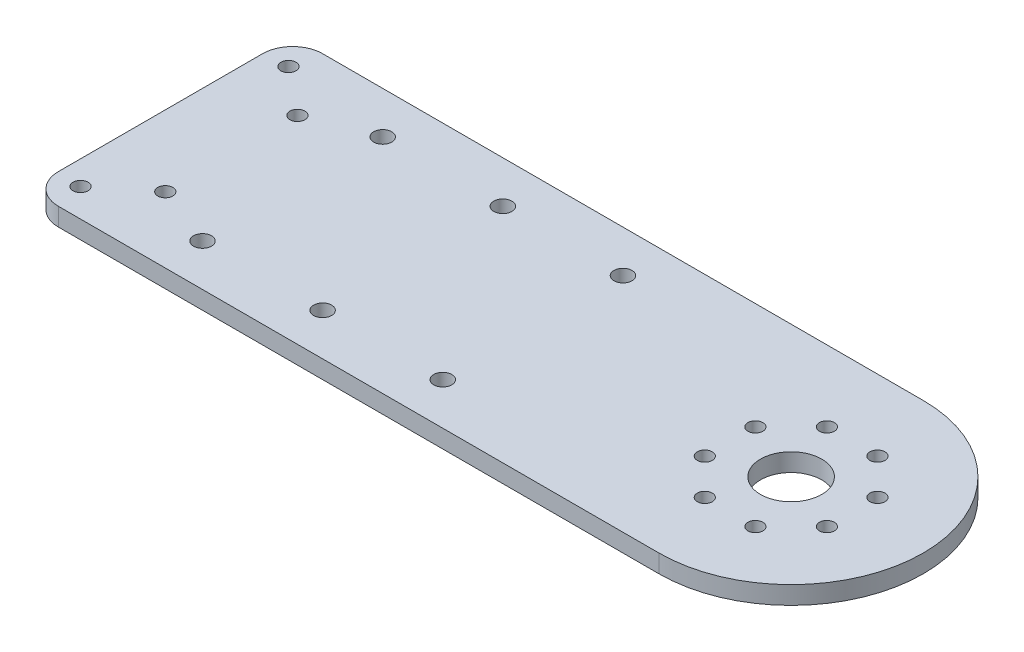
SolidWorks part; units mm, degrees
ref_plane "Front" through (0, 0, 0) normal (0, 0, 1) x (1, 0, 0)
ref_plane "Top" through (0, 0, 0) normal (0, 1, 0) x (1, 0, 0)
ref_plane "Right" through (0, 0, 0) normal (1, 0, 0) x (0, 0, -1)
sketch "Sketch1" plane through (0, 0, 0) normal (0, 1, 0) x (1, 0, 0)
  line L0 (0, 0) -> (128, 0) construction
  line L1 (128, 0) -> (117.8373, 4.2095) construction
  line L2 (128, 22) -> (0, 22)
  line L3 (0, 22) -> (0, 16.4924)
  line L4 (0, -22) -> (128, -22)
  line L5 (0, 0) -> (-13, 0) construction
  line L6 (0, -16.4924) -> (0, -22)
  line L7 (5, 17.3) -> (27, 17.3) construction
  circle A0 centre (128, 0) radius 5.1
  circle A1 centre (117.8373, 4.2095) radius 1.25
  arc A2 (128, -22) -> (128, 22) centre (128, 0) ccw
  circle A3 centre (123.7905, 10.1627) radius 1.25
  circle A4 centre (132.2095, 10.1627) radius 1.25
  circle A5 centre (138.1627, 4.2095) radius 1.25
  circle A6 centre (138.1627, -4.2095) radius 1.25
  circle A7 centre (132.2095, -10.1627) radius 1.25
  arc A8 (0, -16.4924) -> (0, 16.4924) centre (-13, 0) ccw
  circle A9 centre (5, 17.3) radius 1.25
  circle A10 centre (27, 17.3) radius 1.25
  circle A11 centre (27, -17.3) radius 1.25
  circle A12 centre (5, -17.3) radius 1.25
  circle A13 centre (123.7905, -10.1627) radius 1.25
  circle A14 centre (117.8373, -4.2095) radius 1.25
  circle A15 centre (34.8, 11) radius 1.25
  circle A16 centre (34.8, -11) radius 1.25
  point P19 (128, 0)
  dimension "D1" = 2.5
  dimension "D2" = 10.2
  dimension "D4" = 44
  dimension "D9" = 42
  dimension "D10" = 2.5
  dimension "D11" = 2.5
  dimension "D15" = 2.5
  dimension "D16" = 11
  dimension "D17" = 7.8
  dimension "D3" = 11
  dimension "D5" = 22.5
  dimension "D7" = 128
  dimension "D8" = 13
  dimension "D12" = 22
  dimension "D13" = 17.3
  dimension "D14" = 5
  dimension "D6" = 8
extrude "Boss-Extrude1" add sketch "Sketch1" along normal blind 3
fillet "Fillet1" radius 1.5 4 edges at (0, 1.5, -22) (0, 1.5, 22) (0, 1.5, 16.4924) (0, 1.5, -16.4924)
sketch "Sketch2" plane through (0, 3, 0) normal (0, 1, 0) x (1, 0, 0)
  line L0 (0, 0) -> (128, 0) construction
  circle A0 centre (47, 0) radius 1.5
  circle A1 centre (69, 0) radius 1.5
  circle A2 centre (27, -17.3) radius 1.25 construction
  dimension "D1" = 3
  dimension "D2" = 3
  dimension "D3" = 22
  dimension "D4" = 20
extrude "Cut-Extrude1" [suppressed] cut sketch "Sketch2" against normal blind 3
sketch "Sketch3" plane through (0, 3, 0) normal (0, 1, 0) x (1, 0, 0)
  line L0 (1.6969, 15) -> (121.5816, 15) construction
  line L1 (0, 0) -> (128, 0) construction
  arc A0 (0.5333, -16.0577) -> (0.5333, 16.0577) centre (-13, 0) ccw construction
  circle A1 centre (45, 15) radius 1.5
  circle A2 centre (65, 15) radius 1.5
  circle A3 centre (85, 15) radius 1.5
  circle A4 centre (85, -15) radius 1.5
  circle A5 centre (65, -15) radius 1.5
  circle A6 centre (45, -15) radius 1.5
  dimension "D1" = 3
  dimension "D2" = 15
  dimension "D3" = 45
  dimension "D4" = 3
extrude "Cut-Extrude2" cut sketch "Sketch3" against normal blind 3
sketch "Sketch4" plane through (0, 0, 0) normal (0, -1, 0) x (1, 0, 0)
  line L0 (23, 22) -> (23, -22)
  line L1 (1.5, 22) -> (128, 22) construction
  line L2 (128, -22) -> (1.5, -22) construction
  line L3 (23, -22) -> (-10.0456, -22)
  line L4 (-10.0456, -22) -> (-10.0456, 22)
  line L5 (-10.0456, 22) -> (23, 22)
  circle A0 centre (27, 17.3) radius 1.25 construction
  dimension "D1" = 4
extrude "Cut-Extrude3" cut sketch "Sketch4" against normal blind 10
fillet "Fillet2" radius 5 2 edges at (23, 1.5, -22) (23, 1.5, 22)
equation "\"2ю5\"=6.64855"
